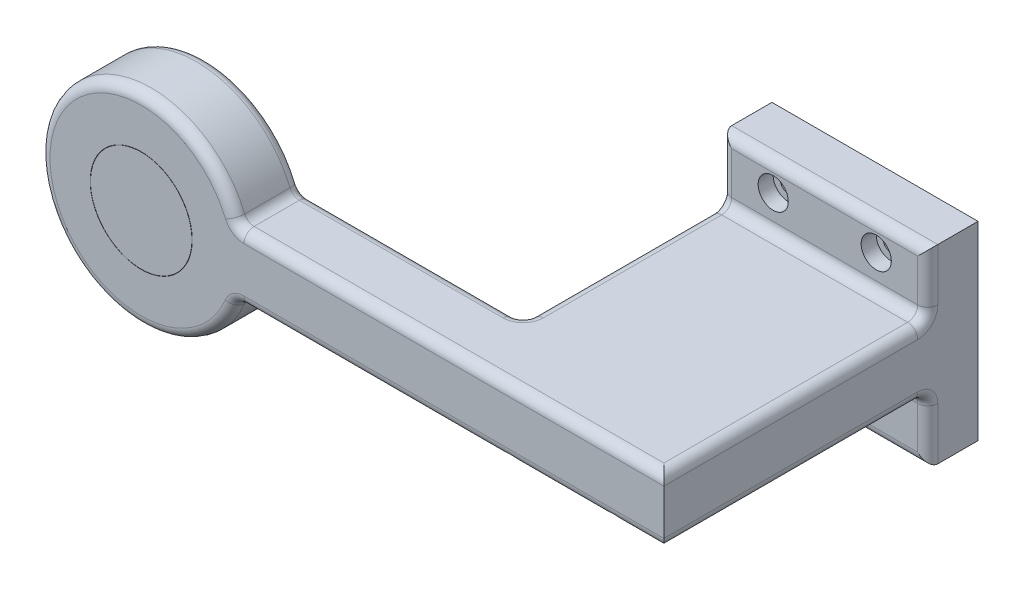
SolidWorks part; units mm, degrees
ref_plane "Front Plane" through (0, 0, 0) normal (1, 0, 0) x (0, 1, 0)
ref_plane "Top Plane" through (0, 0, 0) normal (0, 0, 1) x (0, 1, 0)
ref_plane "Right Plane" through (0, 0, 0) normal (0, 1, 0) x (-1, 0, 0)
sketch "Sketch1" plane through (0, 0, 0) normal (0, 0, 1) x (0, 1, 0)
  line L1 (-18.9, 20.5) -> (18.9, 20.5)
  line L2 (-18.9, 20.5) -> (-18.9, -20.5)
  line L3 (-18.9, -20.5) -> (18.9, -20.5)
  line L4 (18.9, 20.5) -> (18.9, -20.5)
  line L5 (-18.9, 20.5) -> (18.9, -20.5) construction
  line L6 (-18.9, -20.5) -> (18.9, 20.5) construction
  point P0 (0, 0)
  dimension "D1" = 37.8
  dimension "D2" = 41
extrude "Boss-Extrude1" add sketch "Sketch1" along normal blind 10
sketch "Sketch2" plane through (0, 0, 10) normal (0, 0, 1) x (1, 0, 0)
  line L3 (-20.5, 18.9) -> (20.5, 18.9) construction
  line L4 (-20.5, 18.9) -> (-20.5, -18.9) construction
  line L5 (-20.5, -18.9) -> (20.5, -18.9) construction
  line L6 (20.5, 18.9) -> (20.5, -18.9) construction
  line L7 (-20.5, 18.9) -> (20.5, -18.9) construction
  line L8 (-20.5, -18.9) -> (20.5, 18.9) construction
  line L9 (-20.5, 6.5) -> (20.5, 6.5)
  line L10 (-20.5, 6.5) -> (-20.5, -6.5)
  line L11 (-20.5, -6.5) -> (20.5, -6.5)
  line L12 (20.5, 6.5) -> (20.5, -6.5)
  line L13 (-20.5, 6.5) -> (20.5, -6.5) construction
  line L14 (-20.5, -6.5) -> (20.5, 6.5) construction
  point P0 (0, 0)
  point P4 (0, 0)
  point P12 (0, 0)
  dimension "D1" = 13
extrude "Boss-Extrude2" add sketch "Sketch2" along normal blind 52.5
sketch "Sketch3" plane through (-20.5, 0, 0) normal (-1, 0, 0) x (0, -1, 0)
  line L0 (6.5, 62.5) -> (6.5, 10) construction
  line L1 (-6.5, 62.5) -> (6.5, 62.5)
  line L2 (-6.5, 62.5) -> (-6.5, 49.5)
  line L3 (-6.5, 49.5) -> (6.5, 49.5)
  line L4 (6.5, 62.5) -> (6.5, 49.5)
  dimension "D1" = 13
extrude "Boss-Extrude3" add sketch "Sketch3" along normal blind 63
sketch "Sketch4" plane through (0, 0, 62.5) normal (0, 0, 1) x (1, 0, 0)
  line L0 (-83.5, -6.5) -> (-83.5, 6.5) construction
  circle A0 centre (-83.5, 0) radius 10.15
  dimension "D1" = 20.3
extrude "Extrude-Thin1" add sketch "Sketch4" against normal up to surface (13 mm away) thin
sketch "Sketch5" plane through (0, 0, 62.5) normal (0, 0, 1) x (1, 0, 0)
  line L0 (-83.5, -6.5) -> (-83.5, 6.5) construction
  circle A0 centre (-83.5, 0) radius 10.15
  dimension "D1" = 20.3
extrude "Cut-Extrude1" cut sketch "Sketch5" against normal blind 100
sketch "Sketch6" plane through (0, 0, 62.5) normal (0, 0, 1) x (1, 0, 0)
  circle A0 centre (-83.5, 0) radius 10.1
extrude "Boss-Extrude4" add sketch "Sketch6" against normal blind 4
fillet "Fillet2" radius 2 21 edges at (-20.5, 12.7, 10) (20.5, 12.7, 10) (20.5, -12.7, 10) (-20.5, -12.7, 10) (-103.65, 0, 49.5) (-103.65, 0, 62.5) (-20.5, 6.5, 29.75) (0, 6.5, 10) (20.5, 6.5, 36.25) (-21.9636, 6.5, 62.5) (-64.4272, 6.5, 56) (-42.4636, 6.5, 49.5) (20.5, -6.5, 36.25) (0, -6.5, 10) (-20.5, -6.5, 29.75) (-42.4636, -6.5, 49.5) (-64.4272, -6.5, 56) (-21.9636, -6.5, 62.5) (-20.5, 0, 49.5) (0, -18.9, 10) (0, 18.9, 10)
sketch "Sketch7" plane through (0, 0, 0) normal (0, 0, -1) x (1, 0, 0)
  circle A0 centre (-10.25, -13.4179) radius 1.6
  circle A1 centre (-10.25, 8.6024) radius 1.6
  circle A2 centre (10.25, -13.4179) radius 1.6
  circle A3 centre (10.25, 8.6024) radius 1.6
  dimension "D1" = 3.2
extrude "Cut-Extrude2" cut sketch "Sketch7" against normal through all
sketch "Sketch8" plane through (0, 0, 10) normal (0, 0, 1) x (1, 0, 0)
  circle A0 centre (10.25, 13.4179) radius 3
  circle A1 centre (-10.25, 13.4179) radius 3
  circle A2 centre (-10.25, -8.6024) radius 3
  circle A3 centre (10.25, -8.6024) radius 3
  dimension "D1" = 6
extrude "Cut-Extrude3" cut sketch "Sketch8" against normal blind 3 and the other way through all
